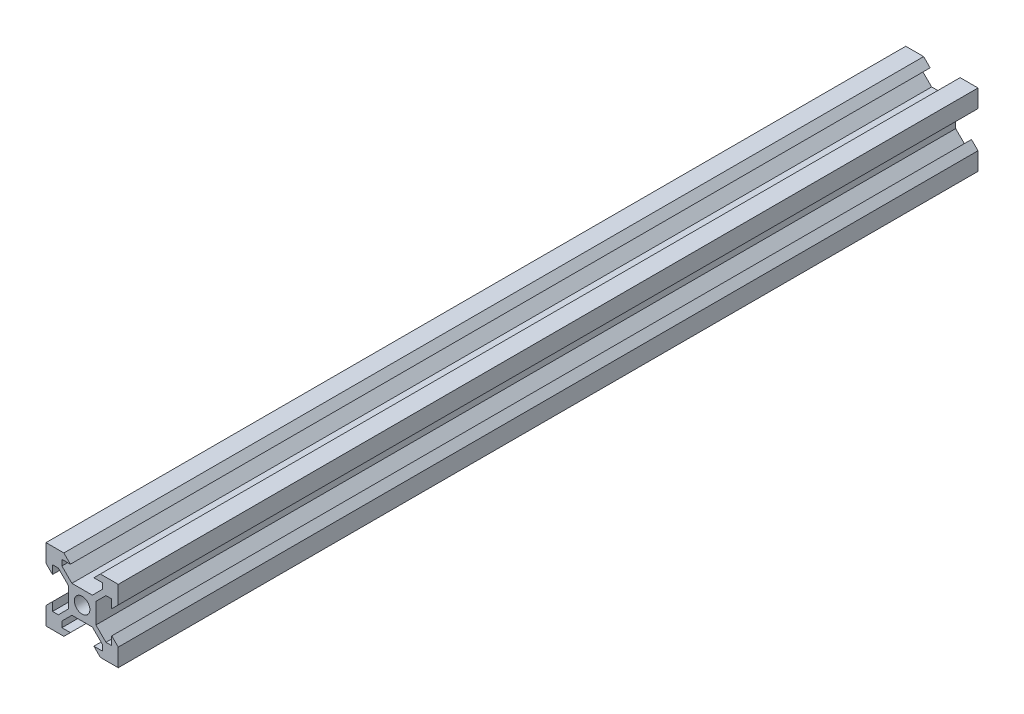
SolidWorks part; units mm, degrees
ref_plane "Alzado" through (0, 0, 0) normal (0, 0, 1) x (1, 0, 0)
ref_plane "Planta" through (0, 0, 0) normal (0, 1, 0) x (1, 0, 0)
ref_plane "Vista lateral" through (0, 0, 0) normal (1, 0, 0) x (0, 0, -1)
sketch "Croquis1" plane through (0, 0, 0) normal (0, 0, 1) x (1, 0, 0)
  line L0 (0, 0) -> (0, -20) construction
  line L2 (0, 0) -> (0, -0.5674)
  line L5 (6.175, -7.1649) -> (6.175, -12.8351)
  line L6 (7.1649, -13.825) -> (12.8351, -13.825)
  line L7 (13.825, -7.1649) -> (13.825, -12.8351)
  line L8 (7.1649, -6.175) -> (12.8351, -6.175)
  line L9 (6.175, -13.825) -> (13.825, -13.825) construction
  line L10 (13.825, -6.175) -> (13.825, -13.825) construction
  line L12 (10, -10) -> (32.1172, -10) construction
  line L13 (13.25, -18.2) -> (15.05, -20)
  line L14 (20, -20) -> (15.6, -20)
  line L15 (20, -20) -> (20, -15.6)
  line L16 (18.2, -15.6) -> (16.5899, -15.6)
  line L32 (15.6, -18.2) -> (15.6, -16.5899)
  line L33 (10, -10) -> (10, -23.2493) construction
  line L34 (4.4, -18.2) -> (4.4, -16.5899)
  line L35 (7.1649, -13.825) -> (4.4, -16.5899)
  line L36 (15.6, -18.2) -> (13.25, -18.2)
  line L38 (15.6, -20) -> (15.05, -20)
  line L40 (15.05, -20) -> (20, -20)
  line L41 (0, -20) -> (20, -20) construction
  line L42 (6.175, -12.8351) -> (3.4101, -15.6)
  line L43 (18.2, -13.25) -> (20, -15.05)
  line L44 (20, -20) -> (18.2, -20)
  line L45 (20, -20) -> (20, -15.05)
  line L48 (20, -15.05) -> (20, -20)
  line L49 (20, 0) -> (20, -20) construction
  line L50 (18.2, -15.6) -> (18.2, -13.25)
  line L51 (12.8351, -13.825) -> (15.6, -16.5899)
  line L52 (13.825, -12.8351) -> (16.5899, -15.6)
  line L53 (1.8, -15.6) -> (3.4101, -15.6)
  line L54 (1.8, -15.6) -> (1.8, -13.25)
  line L55 (1.8, -13.25) -> (0, -15.05)
  line L56 (0, 0) -> (20, 0) construction
  line L57 (0, -20) -> (0, -15.6)
  line L58 (0, -15.6) -> (0, -15.05)
  line L59 (0, -20) -> (4.4, -20)
  line L60 (0, -20) -> (4.95, -20)
  line L61 (6.75, -18.2) -> (4.95, -20)
  line L62 (4.4, -18.2) -> (6.75, -18.2)
  line L63 (1.8, -4.4) -> (3.4101, -4.4)
  line L64 (6.175, -7.1649) -> (3.4101, -4.4)
  line L65 (7.1649, -6.175) -> (4.4, -3.4101)
  line L66 (4.4, -1.8) -> (4.4, -3.4101)
  line L67 (4.4, -1.8) -> (6.75, -1.8)
  line L68 (6.75, -1.8) -> (4.95, 0)
  line L69 (0, 0) -> (4.4, 0)
  line L70 (4.4, 0) -> (4.95, 0)
  line L71 (0, 0) -> (0, -4.4)
  line L72 (0, 0) -> (0, -4.95)
  line L73 (1.8, -6.75) -> (0, -4.95)
  line L74 (1.8, -4.4) -> (1.8, -6.75)
  line L75 (15.6, -1.8) -> (15.6, -3.4101)
  line L76 (12.8351, -6.175) -> (15.6, -3.4101)
  line L77 (13.825, -7.1649) -> (16.5899, -4.4)
  line L78 (18.2, -4.4) -> (16.5899, -4.4)
  line L79 (18.2, -4.4) -> (18.2, -6.75)
  line L80 (18.2, -6.75) -> (20, -4.95)
  line L81 (20, 0) -> (20, -4.4)
  line L82 (20, -4.4) -> (20, -4.95)
  line L83 (20, 0) -> (15.6, 0)
  line L84 (20, 0) -> (15.05, 0)
  line L85 (13.25, -1.8) -> (15.05, 0)
  line L86 (15.6, -1.8) -> (13.25, -1.8)
  line L87 (6.175, -6.175) -> (13.825, -6.175) construction
  line L88 (6.175, -6.175) -> (6.175, -13.825) construction
  circle A0 centre (10, -10) radius 2.15
  point P69 (10, -10)
  dimension "D3" = 4.3
  dimension "D2" = 4
  dimension "D11" = 4.4
  dimension "D15" = 4.4
  dimension "D16" = 6.75
extrude "Saliente-Extruir2" add sketch "Croquis1" along normal blind 238 contours L86 L75 L76 L8 L65 L66 L67 L68 L70 L69 L2 L71 L72 L73 L74 L63 L64 L5 L42 L53 L54 L55 L58 L57 L59 L60 L61 L62 L34 L35 L6 L51 L32 L36 L13 L38 L40 L14 L15 L45 L43 L50 L16 L52 L7 L77 L78 L79 L80 L82 L81
